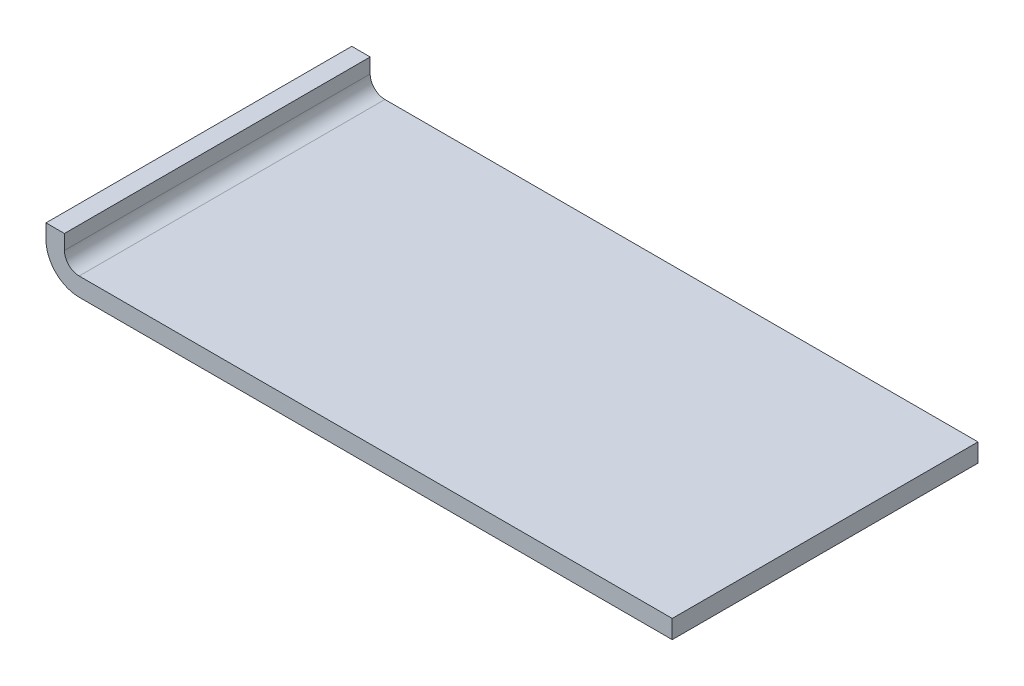
SolidWorks part; units mm, degrees
ref_plane "Front Plane" through (0, 0, 0) normal (0, 0, 1) x (1, 0, 0)
ref_plane "Top Plane" through (0, 0, 0) normal (0, 1, 0) x (1, 0, 0)
ref_plane "Right Plane" through (0, 0, 0) normal (1, 0, 0) x (0, 0, -1)
sketch "Sketch1" plane through (0, 0, 0) normal (0, 0, 1) x (1, 0, 0)
  line L0 (0, 0) -> (0, 0.8)
  line L1 (0, 0.8) -> (-0.5, 0.8)
  line L2 (-0.5, 0.8) -> (-0.5, -0.5)
  line L3 (-0.5, -0.5) -> (16.5, -0.5)
  line L4 (16.5, -0.5) -> (16.5, 0)
  line L5 (16.5, 0) -> (0, 0)
  point P8 (0.3468, 0)
  point P13 (0, 0)
  point P14 (0, 0)
  point P15 (0, 0)
  point P16 (0, 0)
  point P17 (0, 0)
  point P18 (0, 0)
  point P19 (0, 0)
  point P20 (0, 0)
  dimension "D1" = 0.5
  dimension "D2" = 17
  dimension "D3" = 0.8
sketch "Sketch2" plane through (0, 0, 0) normal (0, 0, 1) x (1, 0, 0)
  line L0 (0, 0) -> (0, 0.8) construction
  line L1 (16.5, 0) -> (0, 0) construction
  line L2 (-0.5, 0.8) -> (-0.5, -0.5) construction
  line L3 (-0.5, -0.5) -> (16.5, -0.5) construction
  line L4 (-0.5, 0.4) -> (-0.5, 0.8)
  line L5 (-0.5, 0.8) -> (0, 0.8)
  line L6 (0, 0.8) -> (0, 0.4)
  line L7 (0.4, 0) -> (16.5, 0)
  line L8 (16.5, 0) -> (16.5, -0.5)
  line L9 (16.5, -0.5) -> (0.4, -0.5)
  arc A0 (0, 0.4) -> (0.4, 0) centre (0.4, 0.4) ccw
  arc A1 (-0.5, 0.4) -> (0.4, -0.5) centre (0.4, 0.4) ccw
extrude "Boss-Extrude2" add sketch "Sketch2" along normal mid plane 8.3
